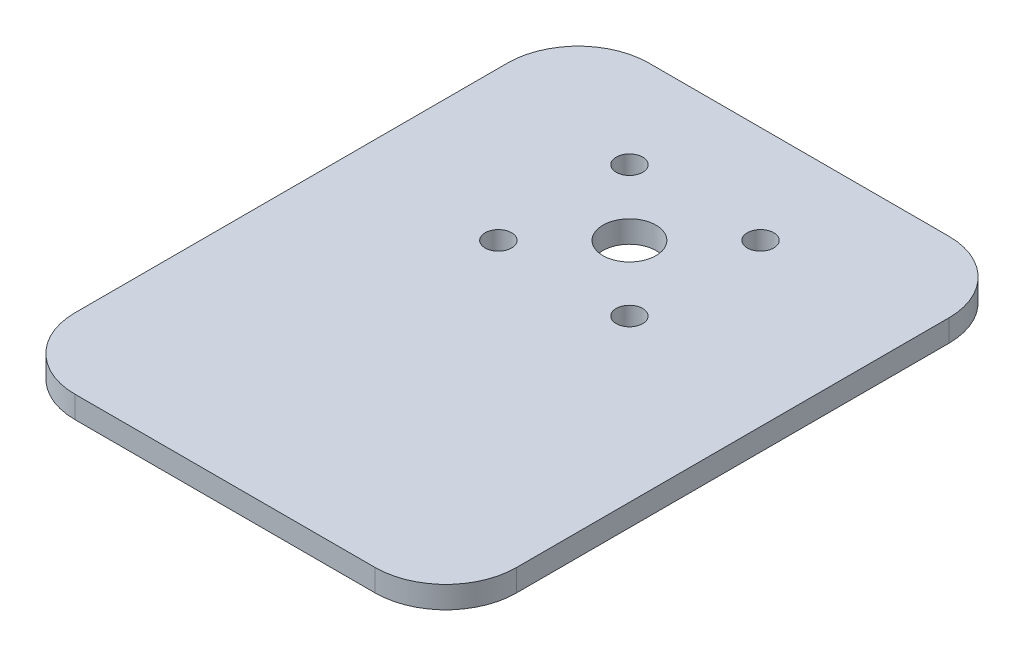
SolidWorks part; units mm, degrees
material "PBT 一般用途"
ref_plane "前视基准面" through (0, 0, 0) normal (0, 0, 1) x (1, 0, 0)
ref_plane "上视基准面" through (0, 0, 0) normal (0, 1, 0) x (1, 0, 0)
ref_plane "右视基准面" through (0, 0, 0) normal (1, 0, 0) x (0, 0, -1)
other "Configuration Table"
sketch "草图1" plane through (0, 0, 0) normal (0, 1, 0) x (1, 0, 0)
  line L1 (-17, -32.5) -> (17, -32.5)
  line L2 (-25, -24.5) -> (-25, 24.5)
  line L3 (-17, 32.5) -> (17, 32.5)
  line L4 (25, -24.5) -> (25, 24.5)
  line L5 (-25, -32.5) -> (25, 32.5) construction
  line L6 (-25, 32.5) -> (25, -32.5) construction
  arc A0 (17, -32.5) -> (25, -24.5) centre (17, -24.5) ccw
  arc A1 (-17, -32.5) -> (-25, -24.5) centre (-17, -24.5) cw
  arc A2 (25, 24.5) -> (17, 32.5) centre (17, 24.5) ccw
  arc A3 (-25, 24.5) -> (-17, 32.5) centre (-17, 24.5) cw
  circle A6 centre (6.7302, 21.4246) radius 1.5
  circle A7 centre (-8.1191, 21.4246) radius 1.5
  circle A8 centre (-8.1191, 6.5754) radius 1.5
  circle A9 centre (6.7302, 6.5754) radius 1.5
  circle A10 centre (-0.6944, 14) radius 3
  point P0 (0, 0)
  point P21 (-8.1191, 21.4246)
  dimension "D3" = 8
  dimension "D4" = 18.5
  dimension "D1" = 50
  dimension "D2" = 65
extrude "凸台-拉伸1" add sketch "草图1" along normal blind 2.5
